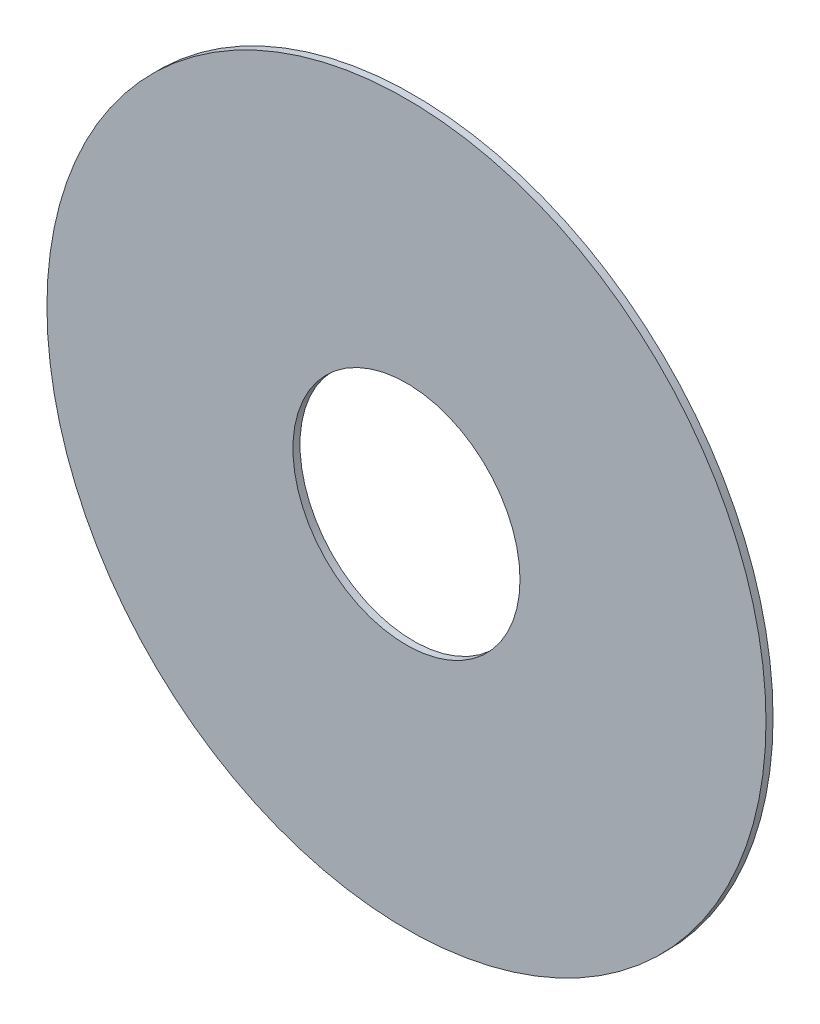
SolidWorks part; units mm, degrees
ref_plane "Front Plane" through (0, 0, 0) normal (0, 0, 1) x (1, 0, 0)
ref_plane "Top Plane" through (0, 0, 0) normal (0, 1, 0) x (1, 0, 0)
ref_plane "Right Plane" through (0, 0, 0) normal (1, 0, 0) x (0, 0, -1)
sketch "Sketch1" plane through (0, 0, 0) normal (0, 0, 1) x (1, 0, 0)
  circle A0 centre (0, 0) radius 241.3
  circle A1 centre (0, 0) radius 76.2
  dimension "D1" = 482.6
  dimension "D2" = 152.4
extrude "Boss-Extrude1" add sketch "Sketch1" along normal blind 4.7371
